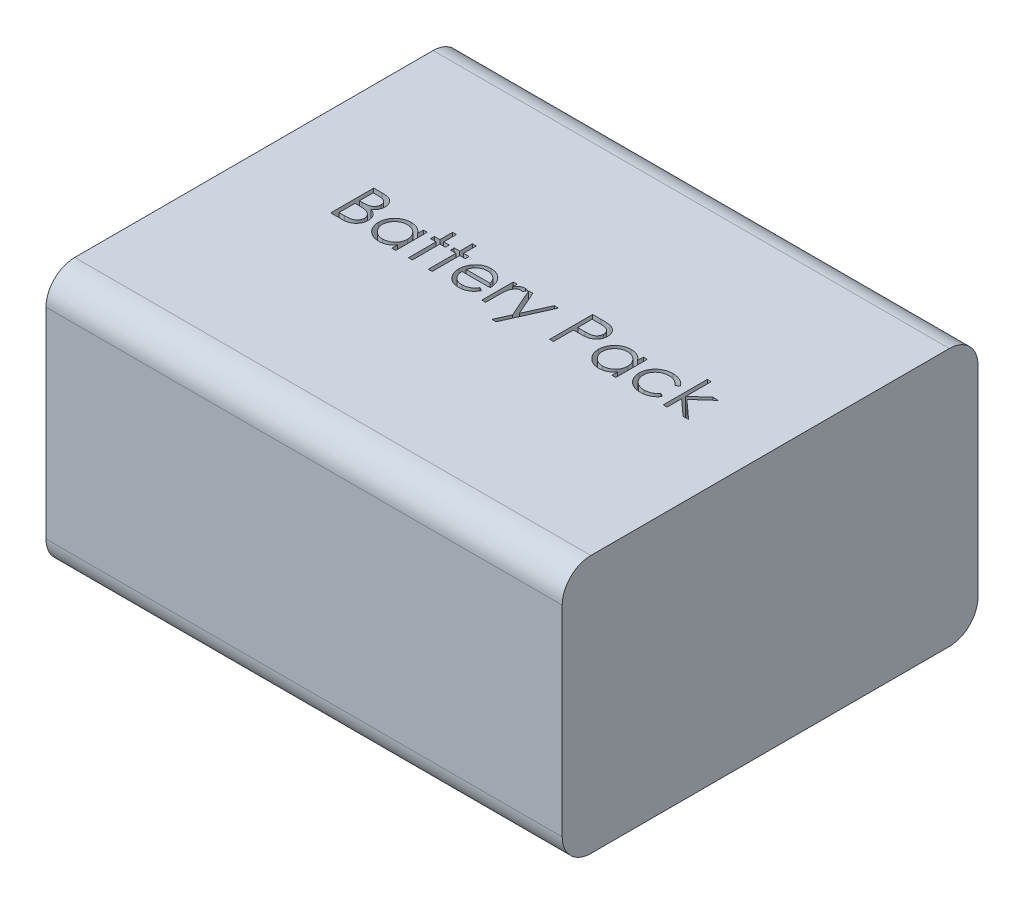
SolidWorks part; units mm, degrees
ref_plane "Front Plane" through (0, 0, 0) normal (0, 0, 1) x (1, 0, 0)
ref_plane "Top Plane" through (0, 0, 0) normal (0, 1, 0) x (1, 0, 0)
ref_plane "Right Plane" through (0, 0, 0) normal (1, 0, 0) x (0, 0, -1)
sketch "Sketch1" plane through (0, 0, 0) normal (0, 1, 0) x (1, 0, 0)
  line L1 (-28.575, 23.0187) -> (28.575, 23.0187)
  line L2 (-28.575, 23.0187) -> (-28.575, -23.0187)
  line L3 (-28.575, -23.0187) -> (28.575, -23.0187)
  line L4 (28.575, 23.0187) -> (28.575, -23.0187)
  dimension "D1" = 57.15
  dimension "D2" = 28.575
  dimension "D3" = 46.0375
  dimension "D4" = 23.0187
extrude "Boss-Extrude1" add sketch "Sketch1" along normal blind 28.575
fillet "Fillet1" radius 3.175 4 edges at (0, 28.575, -23.0187) (0, 0, -23.0187) (0, 0, 23.0187) (0, 28.575, 23.0187)
sketch "Sketch2" plane through (0, 28.575, 0) normal (0, 1, 0) x (1, 0, 0)
  text T0 "Battery Pack" font "Century Gothic" height in points 18
extrude "Cut-Extrude1" cut sketch "Sketch2" against normal blind 2.54
